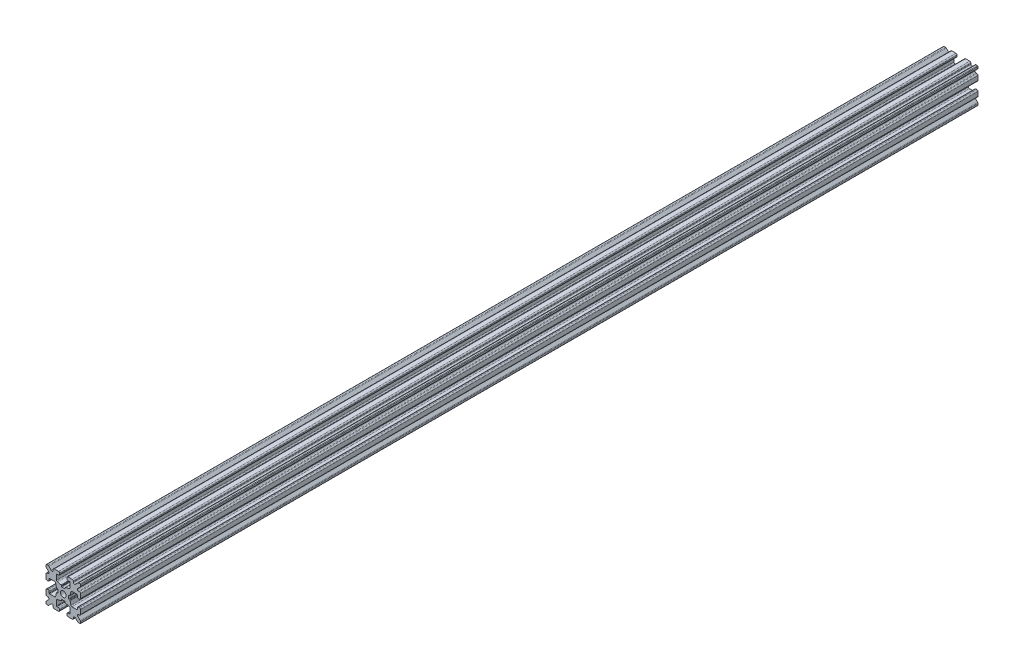
SolidWorks part; units mm, degrees
ref_plane "Alzado" through (0, 0, 0) normal (0, 0, 1) x (1, 0, 0)
ref_plane "Planta" through (0, 0, 0) normal (0, 1, 0) x (1, 0, 0)
ref_plane "Vista lateral" through (0, 0, 0) normal (1, 0, 0) x (0, 0, -1)
ref_plane "Plano1" through (0, 0, -150) normal (0, 0, -1) x (-1, 0, 0)
sketch "Croquis1" plane through (0, 0, -150) normal (0, 0, -1) x (-1, 0, 0)
  line L0 (-2.9, -5.9) -> (-2.9, -3.8003)
  line L1 (-2.5094, -3.3124) -> (-0.9818, -2.97)
  line L2 (-0.8255, -2.7749) -> (-0.8255, -2.5471)
  line L3 (-0.6255, -2.3471) -> (0.6255, -2.3471)
  line L4 (0.8255, -2.5471) -> (0.8255, -2.7749)
  line L5 (0.9818, -2.97) -> (2.5094, -3.3124)
  line L6 (2.9, -3.8003) -> (2.9, -5.9)
  line L7 (2.7, -6.1) -> (2.1, -6.1)
  line L8 (1.6, -6.6) -> (1.6, -7)
  line L9 (2.1, -7.5) -> (3.9, -7.5)
  line L10 (4.4, -7) -> (4.4, -6.6678)
  line L11 (5.2536, -6.3142) -> (6.2929, -7.3536)
  line L12 (6.6464, -7.5) -> (7.25, -7.5)
  line L13 (7.5, -7.25) -> (7.5, -6.6464)
  line L14 (7.3536, -6.2929) -> (6.3142, -5.2536)
  line L15 (6.6678, -4.4) -> (7, -4.4)
  line L16 (7.5, -3.9) -> (7.5, -2.1)
  line L17 (7, -1.6) -> (6.6, -1.6)
  line L18 (6.1, -2.1) -> (6.1, -2.7)
  line L19 (5.9, -2.9) -> (3.8003, -2.9)
  line L20 (3.3124, -2.5094) -> (2.97, -0.9818)
  line L21 (2.7749, -0.8255) -> (2.5471, -0.8255)
  line L22 (2.3471, -0.6255) -> (2.3471, 0.6255)
  line L23 (2.5471, 0.8255) -> (2.7749, 0.8255)
  line L24 (2.97, 0.9818) -> (3.3124, 2.5094)
  line L25 (3.8003, 2.9) -> (5.9, 2.9)
  line L26 (6.1, 2.7) -> (6.1, 2.1)
  line L27 (6.6, 1.6) -> (7, 1.6)
  line L28 (7.5, 2.1) -> (7.5, 3.9)
  line L29 (7, 4.4) -> (6.6678, 4.4)
  line L30 (6.3142, 5.2536) -> (7.3536, 6.2929)
  line L31 (7.5, 6.6464) -> (7.5, 7.25)
  line L32 (7.25, 7.5) -> (6.6464, 7.5)
  line L33 (6.2929, 7.3536) -> (5.2536, 6.3142)
  line L34 (4.4, 6.6678) -> (4.4, 7)
  line L35 (3.9, 7.5) -> (2.1, 7.5)
  line L36 (1.6, 7) -> (1.6, 6.6)
  line L37 (2.1, 6.1) -> (2.7, 6.1)
  line L38 (2.9, 5.9) -> (2.9, 3.8003)
  line L39 (2.5094, 3.3124) -> (0.9818, 2.97)
  line L40 (0.8255, 2.7749) -> (0.8255, 2.5471)
  line L41 (0.6255, 2.3471) -> (-0.6255, 2.3471)
  line L42 (-0.8255, 2.5471) -> (-0.8255, 2.7749)
  line L43 (-0.9818, 2.97) -> (-2.5094, 3.3124)
  line L44 (-2.9, 3.8003) -> (-2.9, 5.9)
  line L45 (-2.7, 6.1) -> (-2.1, 6.1)
  line L46 (-1.6, 6.6) -> (-1.6, 7)
  line L47 (-2.1, 7.5) -> (-3.9, 7.5)
  line L48 (-4.4, 7) -> (-4.4, 6.6678)
  line L49 (-5.2536, 6.3142) -> (-6.2929, 7.3536)
  line L50 (-6.6464, 7.5) -> (-7.25, 7.5)
  line L51 (-7.5, 7.25) -> (-7.5, 6.6464)
  line L52 (-7.3536, 6.2929) -> (-6.3142, 5.2536)
  line L53 (-6.6678, 4.4) -> (-7, 4.4)
  line L54 (-7.5, 3.9) -> (-7.5, 2.1)
  line L55 (-7, 1.6) -> (-6.6, 1.6)
  line L56 (-6.1, 2.1) -> (-6.1, 2.7)
  line L57 (-5.9, 2.9) -> (-3.8003, 2.9)
  line L58 (-3.3124, 2.5094) -> (-2.97, 0.9818)
  line L59 (-2.7749, 0.8255) -> (-2.5471, 0.8255)
  line L60 (-2.3471, 0.6255) -> (-2.3471, -0.6255)
  line L61 (-2.5471, -0.8255) -> (-2.7749, -0.8255)
  line L62 (-2.97, -0.9818) -> (-3.3124, -2.5094)
  line L63 (-3.8003, -2.9) -> (-5.9, -2.9)
  line L64 (-6.1, -2.7) -> (-6.1, -2.1)
  line L65 (-6.6, -1.6) -> (-7, -1.6)
  line L66 (-7.5, -2.1) -> (-7.5, -3.9)
  line L67 (-7, -4.4) -> (-6.6678, -4.4)
  line L68 (-6.3142, -5.2536) -> (-7.3536, -6.2929)
  line L69 (-7.5, -6.6464) -> (-7.5, -7.25)
  line L70 (-7.25, -7.5) -> (-6.6464, -7.5)
  line L71 (-6.2929, -7.3536) -> (-5.2536, -6.3142)
  line L72 (-4.4, -6.6678) -> (-4.4, -7)
  line L73 (-3.9, -7.5) -> (-2.1, -7.5)
  line L74 (-1.6, -7) -> (-1.6, -6.6)
  line L75 (-2.1, -6.1) -> (-2.7, -6.1)
  circle A0 centre (0, 0) radius 1.25
  arc A1 (-2.9, -3.8003) -> (-2.5094, -3.3124) centre (-2.4, -3.8003) cw
  arc A2 (-0.9818, -2.97) -> (-0.8255, -2.7749) centre (-1.0255, -2.7749) ccw
  arc A3 (-0.8255, -2.5471) -> (-0.6255, -2.3471) centre (-0.6255, -2.5471) cw
  arc A4 (0.6255, -2.3471) -> (0.8255, -2.5471) centre (0.6255, -2.5471) cw
  arc A5 (0.8255, -2.7749) -> (0.9818, -2.97) centre (1.0255, -2.7749) ccw
  arc A6 (2.5094, -3.3124) -> (2.9, -3.8003) centre (2.4, -3.8003) cw
  arc A7 (2.9, -5.9) -> (2.7, -6.1) centre (2.7, -5.9) cw
  arc A8 (2.1, -6.1) -> (1.6, -6.6) centre (2.1, -6.6) ccw
  arc A9 (1.6, -7) -> (2.1, -7.5) centre (2.1, -7) ccw
  arc A10 (3.9, -7.5) -> (4.4, -7) centre (3.9, -7) ccw
  arc A11 (4.4, -6.6678) -> (5.2536, -6.3142) centre (4.9, -6.6678) cw
  arc A12 (6.2929, -7.3536) -> (6.6464, -7.5) centre (6.6464, -7) ccw
  arc A13 (7.25, -7.5) -> (7.5, -7.25) centre (7.25, -7.25) ccw
  arc A14 (7.5, -6.6464) -> (7.3536, -6.2929) centre (7, -6.6464) ccw
  arc A15 (6.3142, -5.2536) -> (6.6678, -4.4) centre (6.6678, -4.9) cw
  arc A16 (7, -4.4) -> (7.5, -3.9) centre (7, -3.9) ccw
  arc A17 (7.5, -2.1) -> (7, -1.6) centre (7, -2.1) ccw
  arc A18 (6.6, -1.6) -> (6.1, -2.1) centre (6.6, -2.1) ccw
  arc A19 (6.1, -2.7) -> (5.9, -2.9) centre (5.9, -2.7) cw
  arc A20 (3.8003, -2.9) -> (3.3124, -2.5094) centre (3.8003, -2.4) cw
  arc A21 (2.97, -0.9818) -> (2.7749, -0.8255) centre (2.7749, -1.0255) ccw
  arc A22 (2.5471, -0.8255) -> (2.3471, -0.6255) centre (2.5471, -0.6255) cw
  arc A23 (2.3471, 0.6255) -> (2.5471, 0.8255) centre (2.5471, 0.6255) cw
  arc A24 (2.7749, 0.8255) -> (2.97, 0.9818) centre (2.7749, 1.0255) ccw
  arc A25 (3.3124, 2.5094) -> (3.8003, 2.9) centre (3.8003, 2.4) cw
  arc A26 (5.9, 2.9) -> (6.1, 2.7) centre (5.9, 2.7) cw
  arc A27 (6.1, 2.1) -> (6.6, 1.6) centre (6.6, 2.1) ccw
  arc A28 (7, 1.6) -> (7.5, 2.1) centre (7, 2.1) ccw
  arc A29 (7.5, 3.9) -> (7, 4.4) centre (7, 3.9) ccw
  arc A30 (6.6678, 4.4) -> (6.3142, 5.2536) centre (6.6678, 4.9) cw
  arc A31 (7.3536, 6.2929) -> (7.5, 6.6464) centre (7, 6.6464) ccw
  arc A32 (7.5, 7.25) -> (7.25, 7.5) centre (7.25, 7.25) ccw
  arc A33 (6.6464, 7.5) -> (6.2929, 7.3536) centre (6.6464, 7) ccw
  arc A34 (5.2536, 6.3142) -> (4.4, 6.6678) centre (4.9, 6.6678) cw
  arc A35 (4.4, 7) -> (3.9, 7.5) centre (3.9, 7) ccw
  arc A36 (2.1, 7.5) -> (1.6, 7) centre (2.1, 7) ccw
  arc A37 (1.6, 6.6) -> (2.1, 6.1) centre (2.1, 6.6) ccw
  arc A38 (2.7, 6.1) -> (2.9, 5.9) centre (2.7, 5.9) cw
  arc A39 (2.9, 3.8003) -> (2.5094, 3.3124) centre (2.4, 3.8003) cw
  arc A40 (0.9818, 2.97) -> (0.8255, 2.7749) centre (1.0255, 2.7749) ccw
  arc A41 (0.8255, 2.5471) -> (0.6255, 2.3471) centre (0.6255, 2.5471) cw
  arc A42 (-0.6255, 2.3471) -> (-0.8255, 2.5471) centre (-0.6255, 2.5471) cw
  arc A43 (-0.8255, 2.7749) -> (-0.9818, 2.97) centre (-1.0255, 2.7749) ccw
  arc A44 (-2.5094, 3.3124) -> (-2.9, 3.8003) centre (-2.4, 3.8003) cw
  arc A45 (-2.9, 5.9) -> (-2.7, 6.1) centre (-2.7, 5.9) cw
  arc A46 (-2.1, 6.1) -> (-1.6, 6.6) centre (-2.1, 6.6) ccw
  arc A47 (-1.6, 7) -> (-2.1, 7.5) centre (-2.1, 7) ccw
  arc A48 (-3.9, 7.5) -> (-4.4, 7) centre (-3.9, 7) ccw
  arc A49 (-4.4, 6.6678) -> (-5.2536, 6.3142) centre (-4.9, 6.6678) cw
  arc A50 (-6.2929, 7.3536) -> (-6.6464, 7.5) centre (-6.6464, 7) ccw
  arc A51 (-7.25, 7.5) -> (-7.5, 7.25) centre (-7.25, 7.25) ccw
  arc A52 (-7.5, 6.6464) -> (-7.3536, 6.2929) centre (-7, 6.6464) ccw
  arc A53 (-6.3142, 5.2536) -> (-6.6678, 4.4) centre (-6.6678, 4.9) cw
  arc A54 (-7, 4.4) -> (-7.5, 3.9) centre (-7, 3.9) ccw
  arc A55 (-7.5, 2.1) -> (-7, 1.6) centre (-7, 2.1) ccw
  arc A56 (-6.6, 1.6) -> (-6.1, 2.1) centre (-6.6, 2.1) ccw
  arc A57 (-6.1, 2.7) -> (-5.9, 2.9) centre (-5.9, 2.7) cw
  arc A58 (-3.8003, 2.9) -> (-3.3124, 2.5094) centre (-3.8003, 2.4) cw
  arc A59 (-2.97, 0.9818) -> (-2.7749, 0.8255) centre (-2.7749, 1.0255) ccw
  arc A60 (-2.5471, 0.8255) -> (-2.3471, 0.6255) centre (-2.5471, 0.6255) cw
  arc A61 (-2.3471, -0.6255) -> (-2.5471, -0.8255) centre (-2.5471, -0.6255) cw
  arc A62 (-2.7749, -0.8255) -> (-2.97, -0.9818) centre (-2.7749, -1.0255) ccw
  arc A63 (-3.3124, -2.5094) -> (-3.8003, -2.9) centre (-3.8003, -2.4) cw
  arc A64 (-5.9, -2.9) -> (-6.1, -2.7) centre (-5.9, -2.7) cw
  arc A65 (-6.1, -2.1) -> (-6.6, -1.6) centre (-6.6, -2.1) ccw
  arc A66 (-7, -1.6) -> (-7.5, -2.1) centre (-7, -2.1) ccw
  arc A67 (-7.5, -3.9) -> (-7, -4.4) centre (-7, -3.9) ccw
  arc A68 (-6.6678, -4.4) -> (-6.3142, -5.2536) centre (-6.6678, -4.9) cw
  arc A69 (-7.3536, -6.2929) -> (-7.5, -6.6464) centre (-7, -6.6464) ccw
  arc A70 (-7.5, -7.25) -> (-7.25, -7.5) centre (-7.25, -7.25) ccw
  arc A71 (-6.6464, -7.5) -> (-6.2929, -7.3536) centre (-6.6464, -7) ccw
  arc A72 (-5.2536, -6.3142) -> (-4.4, -6.6678) centre (-4.9, -6.6678) cw
  arc A73 (-4.4, -7) -> (-3.9, -7.5) centre (-3.9, -7) ccw
  arc A74 (-2.1, -7.5) -> (-1.6, -7) centre (-2.1, -7) ccw
  arc A75 (-1.6, -6.6) -> (-2.1, -6.1) centre (-2.1, -6.6) ccw
  arc A76 (-2.7, -6.1) -> (-2.9, -5.9) centre (-2.7, -5.9) cw
extrude "Saliente-Extruir1" add sketch "Croquis1" against normal blind 300
sketch "Croquis2" plane through (0, 0, 150) normal (0, 0, 1) x (1, 0, 0)
  line L76 (2.7, -6.1) -> (2.1, -6.1)
  line L77 (1.6, -6.6) -> (1.6, -7)
  line L78 (2.1, -7.5) -> (3.9, -7.5)
  line L79 (4.4, -7) -> (4.4, -6.6678)
  line L80 (5.2536, -6.3142) -> (6.2929, -7.3536)
  line L81 (6.6464, -7.5) -> (7.25, -7.5)
  line L82 (7.5, -7.25) -> (7.5, -6.6464)
  line L83 (7.3536, -6.2929) -> (6.3142, -5.2536)
  line L84 (6.6678, -4.4) -> (7, -4.4)
  line L85 (7.5, -3.9) -> (7.5, -2.1)
  line L86 (7, -1.6) -> (6.6, -1.6)
  line L87 (6.1, -2.1) -> (6.1, -2.7)
  line L88 (5.9, -2.9) -> (3.8003, -2.9)
  line L89 (3.3124, -2.5094) -> (2.97, -0.9818)
  line L90 (2.7749, -0.8255) -> (2.5471, -0.8255)
  line L91 (2.3471, -0.6255) -> (2.3471, 0.6255)
  line L92 (2.5471, 0.8255) -> (2.7749, 0.8255)
  line L93 (2.97, 0.9818) -> (3.3124, 2.5094)
  line L94 (3.8003, 2.9) -> (5.9, 2.9)
  line L95 (6.1, 2.7) -> (6.1, 2.1)
  line L96 (6.6, 1.6) -> (7, 1.6)
  line L97 (7.5, 2.1) -> (7.5, 3.9)
  line L98 (7, 4.4) -> (6.6678, 4.4)
  line L99 (6.3142, 5.2536) -> (7.3536, 6.2929)
  line L100 (7.5, 6.6464) -> (7.5, 7.25)
  line L101 (7.25, 7.5) -> (6.6464, 7.5)
  line L102 (6.2929, 7.3536) -> (5.2536, 6.3142)
  line L103 (4.4, 6.6678) -> (4.4, 7)
  line L104 (3.9, 7.5) -> (2.1, 7.5)
  line L105 (1.6, 7) -> (1.6, 6.6)
  line L106 (2.1, 6.1) -> (2.7, 6.1)
  line L107 (2.9, 5.9) -> (2.9, 3.8003)
  line L108 (2.5094, 3.3124) -> (0.9818, 2.97)
  line L109 (0.8255, 2.7749) -> (0.8255, 2.5471)
  line L110 (0.6255, 2.3471) -> (-0.6255, 2.3471)
  line L111 (-0.8255, 2.5471) -> (-0.8255, 2.7749)
  line L112 (-0.9818, 2.97) -> (-2.5094, 3.3124)
  line L113 (-2.9, 3.8003) -> (-2.9, 5.9)
  line L114 (-2.7, 6.1) -> (-2.1, 6.1)
  line L115 (-1.6, 6.6) -> (-1.6, 7)
  line L116 (-2.1, 7.5) -> (-3.9, 7.5)
  line L117 (-4.4, 7) -> (-4.4, 6.6678)
  line L118 (-5.2536, 6.3142) -> (-6.2929, 7.3536)
  line L119 (-6.6464, 7.5) -> (-7.25, 7.5)
  line L120 (-7.5, 7.25) -> (-7.5, 6.6464)
  line L121 (-7.3536, 6.2929) -> (-6.3142, 5.2536)
  line L122 (-6.6678, 4.4) -> (-7, 4.4)
  line L123 (-7.5, 3.9) -> (-7.5, 2.1)
  line L124 (-7, 1.6) -> (-6.6, 1.6)
  line L125 (-6.1, 2.1) -> (-6.1, 2.7)
  line L126 (-5.9, 2.9) -> (-3.8003, 2.9)
  line L127 (-3.3124, 2.5094) -> (-2.97, 0.9818)
  line L128 (-2.7749, 0.8255) -> (-2.5471, 0.8255)
  line L129 (-2.3471, 0.6255) -> (-2.3471, -0.6255)
  line L130 (-2.5471, -0.8255) -> (-2.7749, -0.8255)
  line L131 (-2.97, -0.9818) -> (-3.3124, -2.5094)
  line L132 (-3.8003, -2.9) -> (-5.9, -2.9)
  line L133 (-6.1, -2.7) -> (-6.1, -2.1)
  line L134 (-6.6, -1.6) -> (-7, -1.6)
  line L135 (-7.5, -2.1) -> (-7.5, -3.9)
  line L136 (-7, -4.4) -> (-6.6678, -4.4)
  line L137 (-6.3142, -5.2536) -> (-7.3536, -6.2929)
  line L138 (-7.5, -6.6464) -> (-7.5, -7.25)
  line L139 (-7.25, -7.5) -> (-6.6464, -7.5)
  line L140 (-6.2929, -7.3536) -> (-5.2536, -6.3142)
  line L141 (-4.4, -6.6678) -> (-4.4, -7)
  line L142 (-3.9, -7.5) -> (-2.1, -7.5)
  line L143 (-1.6, -7) -> (-1.6, -6.6)
  line L144 (-2.1, -6.1) -> (-2.7, -6.1)
  line L145 (-2.9, -5.9) -> (-2.9, -3.8003)
  line L146 (-2.5094, -3.3124) -> (-0.9818, -2.97)
  line L147 (-0.8255, -2.7749) -> (-0.8255, -2.5471)
  line L148 (-0.6255, -2.3471) -> (0.6255, -2.3471)
  line L149 (0.8255, -2.5471) -> (0.8255, -2.7749)
  line L150 (0.9818, -2.97) -> (2.5094, -3.3124)
  line L151 (2.9, -3.8003) -> (2.9, -5.9)
  line L152 (2.7, -6.1) -> (2.1, -6.1)
  line L153 (1.6, -6.6) -> (1.6, -7)
  line L154 (2.1, -7.5) -> (3.9, -7.5)
  line L155 (4.4, -7) -> (4.4, -6.6678)
  line L156 (5.2536, -6.3142) -> (6.2929, -7.3536)
  line L157 (6.6464, -7.5) -> (7.25, -7.5)
  line L158 (7.5, -7.25) -> (7.5, -6.6464)
  line L159 (7.3536, -6.2929) -> (6.3142, -5.2536)
  line L160 (6.6678, -4.4) -> (7, -4.4)
  line L161 (7.5, -3.9) -> (7.5, -2.1)
  line L162 (7, -1.6) -> (6.6, -1.6)
  line L163 (6.1, -2.1) -> (6.1, -2.7)
  line L164 (5.9, -2.9) -> (3.8003, -2.9)
  line L165 (3.3124, -2.5094) -> (2.97, -0.9818)
  line L166 (2.7749, -0.8255) -> (2.5471, -0.8255)
  line L167 (2.3471, -0.6255) -> (2.3471, 0.6255)
  line L168 (2.5471, 0.8255) -> (2.7749, 0.8255)
  line L169 (2.97, 0.9818) -> (3.3124, 2.5094)
  line L170 (3.8003, 2.9) -> (5.9, 2.9)
  line L171 (6.1, 2.7) -> (6.1, 2.1)
  line L172 (6.6, 1.6) -> (7, 1.6)
  line L173 (7.5, 2.1) -> (7.5, 3.9)
  line L174 (7, 4.4) -> (6.6678, 4.4)
  line L175 (6.3142, 5.2536) -> (7.3536, 6.2929)
  line L176 (7.5, 6.6464) -> (7.5, 7.25)
  line L177 (7.25, 7.5) -> (6.6464, 7.5)
  line L178 (6.2929, 7.3536) -> (5.2536, 6.3142)
  line L179 (4.4, 6.6678) -> (4.4, 7)
  line L180 (3.9, 7.5) -> (2.1, 7.5)
  line L181 (1.6, 7) -> (1.6, 6.6)
  line L182 (2.1, 6.1) -> (2.7, 6.1)
  line L183 (2.9, 5.9) -> (2.9, 3.8003)
  line L184 (2.5094, 3.3124) -> (0.9818, 2.97)
  line L185 (0.8255, 2.7749) -> (0.8255, 2.5471)
  line L186 (0.6255, 2.3471) -> (-0.6255, 2.3471)
  line L187 (-0.8255, 2.5471) -> (-0.8255, 2.7749)
  line L188 (-0.9818, 2.97) -> (-2.5094, 3.3124)
  line L189 (-2.9, 3.8003) -> (-2.9, 5.9)
  line L190 (-2.7, 6.1) -> (-2.1, 6.1)
  line L191 (-1.6, 6.6) -> (-1.6, 7)
  line L192 (-2.1, 7.5) -> (-3.9, 7.5)
  line L193 (-4.4, 7) -> (-4.4, 6.6678)
  line L194 (-5.2536, 6.3142) -> (-6.2929, 7.3536)
  line L195 (-6.6464, 7.5) -> (-7.25, 7.5)
  line L196 (-7.5, 7.25) -> (-7.5, 6.6464)
  line L197 (-7.3536, 6.2929) -> (-6.3142, 5.2536)
  line L198 (-6.6678, 4.4) -> (-7, 4.4)
  line L199 (-7.5, 3.9) -> (-7.5, 2.1)
  line L200 (-7, 1.6) -> (-6.6, 1.6)
  line L201 (-6.1, 2.1) -> (-6.1, 2.7)
  line L202 (-5.9, 2.9) -> (-3.8003, 2.9)
  line L203 (-3.3124, 2.5094) -> (-2.97, 0.9818)
  line L204 (-2.7749, 0.8255) -> (-2.5471, 0.8255)
  line L205 (-2.3471, 0.6255) -> (-2.3471, -0.6255)
  line L206 (-2.5471, -0.8255) -> (-2.7749, -0.8255)
  line L207 (-2.97, -0.9818) -> (-3.3124, -2.5094)
  line L208 (-3.8003, -2.9) -> (-5.9, -2.9)
  line L209 (-6.1, -2.7) -> (-6.1, -2.1)
  line L210 (-6.6, -1.6) -> (-7, -1.6)
  line L211 (-7.5, -2.1) -> (-7.5, -3.9)
  line L212 (-7, -4.4) -> (-6.6678, -4.4)
  line L213 (-6.3142, -5.2536) -> (-7.3536, -6.2929)
  line L214 (-7.5, -6.6464) -> (-7.5, -7.25)
  line L215 (-7.25, -7.5) -> (-6.6464, -7.5)
  line L216 (-6.2929, -7.3536) -> (-5.2536, -6.3142)
  line L217 (-4.4, -6.6678) -> (-4.4, -7)
  line L218 (-3.9, -7.5) -> (-2.1, -7.5)
  line L219 (-1.6, -7) -> (-1.6, -6.6)
  line L220 (-2.1, -6.1) -> (-2.7, -6.1)
  line L221 (-2.9, -5.9) -> (-2.9, -3.8003)
  line L222 (-2.5094, -3.3124) -> (-0.9818, -2.97)
  line L223 (-0.8255, -2.7749) -> (-0.8255, -2.5471)
  line L224 (-0.6255, -2.3471) -> (0.6255, -2.3471)
  line L225 (0.8255, -2.5471) -> (0.8255, -2.7749)
  line L226 (0.9818, -2.97) -> (2.5094, -3.3124)
  line L227 (2.9, -3.8003) -> (2.9, -5.9)
  circle A0 centre (0, 0) radius 1.25 construction
  circle A1 centre (0, 0) radius 1.25
  arc A76 (2.7, -6.1) -> (2.9, -5.9) centre (2.7, -5.9) ccw
  arc A77 (2.1, -6.1) -> (1.6, -6.6) centre (2.1, -6.6) ccw
  arc A78 (1.6, -7) -> (2.1, -7.5) centre (2.1, -7) ccw
  arc A79 (3.9, -7.5) -> (4.4, -7) centre (3.9, -7) ccw
  arc A80 (5.2536, -6.3142) -> (4.4, -6.6678) centre (4.9, -6.6678) ccw
  arc A81 (6.2929, -7.3536) -> (6.6464, -7.5) centre (6.6464, -7) ccw
  arc A82 (7.25, -7.5) -> (7.5, -7.25) centre (7.25, -7.25) ccw
  arc A83 (7.5, -6.6464) -> (7.3536, -6.2929) centre (7, -6.6464) ccw
  arc A84 (6.6678, -4.4) -> (6.3142, -5.2536) centre (6.6678, -4.9) ccw
  arc A85 (7, -4.4) -> (7.5, -3.9) centre (7, -3.9) ccw
  arc A86 (7.5, -2.1) -> (7, -1.6) centre (7, -2.1) ccw
  arc A87 (6.6, -1.6) -> (6.1, -2.1) centre (6.6, -2.1) ccw
  arc A88 (5.9, -2.9) -> (6.1, -2.7) centre (5.9, -2.7) ccw
  arc A89 (3.3124, -2.5094) -> (3.8003, -2.9) centre (3.8003, -2.4) ccw
  arc A90 (2.97, -0.9818) -> (2.7749, -0.8255) centre (2.7749, -1.0255) ccw
  arc A91 (2.3471, -0.6255) -> (2.5471, -0.8255) centre (2.5471, -0.6255) ccw
  arc A92 (2.5471, 0.8255) -> (2.3471, 0.6255) centre (2.5471, 0.6255) ccw
  arc A93 (2.7749, 0.8255) -> (2.97, 0.9818) centre (2.7749, 1.0255) ccw
  arc A94 (3.8003, 2.9) -> (3.3124, 2.5094) centre (3.8003, 2.4) ccw
  arc A95 (6.1, 2.7) -> (5.9, 2.9) centre (5.9, 2.7) ccw
  arc A96 (6.1, 2.1) -> (6.6, 1.6) centre (6.6, 2.1) ccw
  arc A97 (7, 1.6) -> (7.5, 2.1) centre (7, 2.1) ccw
  arc A98 (7.5, 3.9) -> (7, 4.4) centre (7, 3.9) ccw
  arc A99 (6.3142, 5.2536) -> (6.6678, 4.4) centre (6.6678, 4.9) ccw
  arc A100 (7.3536, 6.2929) -> (7.5, 6.6464) centre (7, 6.6464) ccw
  arc A101 (7.5, 7.25) -> (7.25, 7.5) centre (7.25, 7.25) ccw
  arc A102 (6.6464, 7.5) -> (6.2929, 7.3536) centre (6.6464, 7) ccw
  arc A103 (4.4, 6.6678) -> (5.2536, 6.3142) centre (4.9, 6.6678) ccw
  arc A104 (4.4, 7) -> (3.9, 7.5) centre (3.9, 7) ccw
  arc A105 (2.1, 7.5) -> (1.6, 7) centre (2.1, 7) ccw
  arc A106 (1.6, 6.6) -> (2.1, 6.1) centre (2.1, 6.6) ccw
  arc A107 (2.9, 5.9) -> (2.7, 6.1) centre (2.7, 5.9) ccw
  arc A108 (2.5094, 3.3124) -> (2.9, 3.8003) centre (2.4, 3.8003) ccw
  arc A109 (0.9818, 2.97) -> (0.8255, 2.7749) centre (1.0255, 2.7749) ccw
  arc A110 (0.6255, 2.3471) -> (0.8255, 2.5471) centre (0.6255, 2.5471) ccw
  arc A111 (-0.8255, 2.5471) -> (-0.6255, 2.3471) centre (-0.6255, 2.5471) ccw
  arc A112 (-0.8255, 2.7749) -> (-0.9818, 2.97) centre (-1.0255, 2.7749) ccw
  arc A113 (-2.9, 3.8003) -> (-2.5094, 3.3124) centre (-2.4, 3.8003) ccw
  arc A114 (-2.7, 6.1) -> (-2.9, 5.9) centre (-2.7, 5.9) ccw
  arc A115 (-2.1, 6.1) -> (-1.6, 6.6) centre (-2.1, 6.6) ccw
  arc A116 (-1.6, 7) -> (-2.1, 7.5) centre (-2.1, 7) ccw
  arc A117 (-3.9, 7.5) -> (-4.4, 7) centre (-3.9, 7) ccw
  arc A118 (-5.2536, 6.3142) -> (-4.4, 6.6678) centre (-4.9, 6.6678) ccw
  arc A119 (-6.2929, 7.3536) -> (-6.6464, 7.5) centre (-6.6464, 7) ccw
  arc A120 (-7.25, 7.5) -> (-7.5, 7.25) centre (-7.25, 7.25) ccw
  arc A121 (-7.5, 6.6464) -> (-7.3536, 6.2929) centre (-7, 6.6464) ccw
  arc A122 (-6.6678, 4.4) -> (-6.3142, 5.2536) centre (-6.6678, 4.9) ccw
  arc A123 (-7, 4.4) -> (-7.5, 3.9) centre (-7, 3.9) ccw
  arc A124 (-7.5, 2.1) -> (-7, 1.6) centre (-7, 2.1) ccw
  arc A125 (-6.6, 1.6) -> (-6.1, 2.1) centre (-6.6, 2.1) ccw
  arc A126 (-5.9, 2.9) -> (-6.1, 2.7) centre (-5.9, 2.7) ccw
  arc A127 (-3.3124, 2.5094) -> (-3.8003, 2.9) centre (-3.8003, 2.4) ccw
  arc A128 (-2.97, 0.9818) -> (-2.7749, 0.8255) centre (-2.7749, 1.0255) ccw
  arc A129 (-2.3471, 0.6255) -> (-2.5471, 0.8255) centre (-2.5471, 0.6255) ccw
  arc A130 (-2.5471, -0.8255) -> (-2.3471, -0.6255) centre (-2.5471, -0.6255) ccw
  arc A131 (-2.7749, -0.8255) -> (-2.97, -0.9818) centre (-2.7749, -1.0255) ccw
  arc A132 (-3.8003, -2.9) -> (-3.3124, -2.5094) centre (-3.8003, -2.4) ccw
  arc A133 (-6.1, -2.7) -> (-5.9, -2.9) centre (-5.9, -2.7) ccw
  arc A134 (-6.1, -2.1) -> (-6.6, -1.6) centre (-6.6, -2.1) ccw
  arc A135 (-7, -1.6) -> (-7.5, -2.1) centre (-7, -2.1) ccw
  arc A136 (-7.5, -3.9) -> (-7, -4.4) centre (-7, -3.9) ccw
  arc A137 (-6.3142, -5.2536) -> (-6.6678, -4.4) centre (-6.6678, -4.9) ccw
  arc A138 (-7.3536, -6.2929) -> (-7.5, -6.6464) centre (-7, -6.6464) ccw
  arc A139 (-7.5, -7.25) -> (-7.25, -7.5) centre (-7.25, -7.25) ccw
  arc A140 (-6.6464, -7.5) -> (-6.2929, -7.3536) centre (-6.6464, -7) ccw
  arc A141 (-4.4, -6.6678) -> (-5.2536, -6.3142) centre (-4.9, -6.6678) ccw
  arc A142 (-4.4, -7) -> (-3.9, -7.5) centre (-3.9, -7) ccw
  arc A143 (-2.1, -7.5) -> (-1.6, -7) centre (-2.1, -7) ccw
  arc A144 (-1.6, -6.6) -> (-2.1, -6.1) centre (-2.1, -6.6) ccw
  arc A145 (-2.9, -5.9) -> (-2.7, -6.1) centre (-2.7, -5.9) ccw
  arc A146 (-2.5094, -3.3124) -> (-2.9, -3.8003) centre (-2.4, -3.8003) ccw
  arc A147 (-0.9818, -2.97) -> (-0.8255, -2.7749) centre (-1.0255, -2.7749) ccw
  arc A148 (-0.6255, -2.3471) -> (-0.8255, -2.5471) centre (-0.6255, -2.5471) ccw
  arc A149 (0.8255, -2.5471) -> (0.6255, -2.3471) centre (0.6255, -2.5471) ccw
  arc A150 (0.8255, -2.7749) -> (0.9818, -2.97) centre (1.0255, -2.7749) ccw
  arc A151 (2.9, -3.8003) -> (2.5094, -3.3124) centre (2.4, -3.8003) ccw
  arc A152 (2.7, -6.1) -> (2.9, -5.9) centre (2.7, -5.9) ccw
  arc A153 (2.1, -6.1) -> (1.6, -6.6) centre (2.1, -6.6) ccw
  arc A154 (1.6, -7) -> (2.1, -7.5) centre (2.1, -7) ccw
  arc A155 (3.9, -7.5) -> (4.4, -7) centre (3.9, -7) ccw
  arc A156 (5.2536, -6.3142) -> (4.4, -6.6678) centre (4.9, -6.6678) ccw
  arc A157 (6.2929, -7.3536) -> (6.6464, -7.5) centre (6.6464, -7) ccw
  arc A158 (7.25, -7.5) -> (7.5, -7.25) centre (7.25, -7.25) ccw
  arc A159 (7.5, -6.6464) -> (7.3536, -6.2929) centre (7, -6.6464) ccw
  arc A160 (6.6678, -4.4) -> (6.3142, -5.2536) centre (6.6678, -4.9) ccw
  arc A161 (7, -4.4) -> (7.5, -3.9) centre (7, -3.9) ccw
  arc A162 (7.5, -2.1) -> (7, -1.6) centre (7, -2.1) ccw
  arc A163 (6.6, -1.6) -> (6.1, -2.1) centre (6.6, -2.1) ccw
  arc A164 (5.9, -2.9) -> (6.1, -2.7) centre (5.9, -2.7) ccw
  arc A165 (3.3124, -2.5094) -> (3.8003, -2.9) centre (3.8003, -2.4) ccw
  arc A166 (2.97, -0.9818) -> (2.7749, -0.8255) centre (2.7749, -1.0255) ccw
  arc A167 (2.3471, -0.6255) -> (2.5471, -0.8255) centre (2.5471, -0.6255) ccw
  arc A168 (2.5471, 0.8255) -> (2.3471, 0.6255) centre (2.5471, 0.6255) ccw
  arc A169 (2.7749, 0.8255) -> (2.97, 0.9818) centre (2.7749, 1.0255) ccw
  arc A170 (3.8003, 2.9) -> (3.3124, 2.5094) centre (3.8003, 2.4) ccw
  arc A171 (6.1, 2.7) -> (5.9, 2.9) centre (5.9, 2.7) ccw
  arc A172 (6.1, 2.1) -> (6.6, 1.6) centre (6.6, 2.1) ccw
  arc A173 (7, 1.6) -> (7.5, 2.1) centre (7, 2.1) ccw
  arc A174 (7.5, 3.9) -> (7, 4.4) centre (7, 3.9) ccw
  arc A175 (6.3142, 5.2536) -> (6.6678, 4.4) centre (6.6678, 4.9) ccw
  arc A176 (7.3536, 6.2929) -> (7.5, 6.6464) centre (7, 6.6464) ccw
  arc A177 (7.5, 7.25) -> (7.25, 7.5) centre (7.25, 7.25) ccw
  arc A178 (6.6464, 7.5) -> (6.2929, 7.3536) centre (6.6464, 7) ccw
  arc A179 (4.4, 6.6678) -> (5.2536, 6.3142) centre (4.9, 6.6678) ccw
  arc A180 (4.4, 7) -> (3.9, 7.5) centre (3.9, 7) ccw
  arc A181 (2.1, 7.5) -> (1.6, 7) centre (2.1, 7) ccw
  arc A182 (1.6, 6.6) -> (2.1, 6.1) centre (2.1, 6.6) ccw
  arc A183 (2.9, 5.9) -> (2.7, 6.1) centre (2.7, 5.9) ccw
  arc A184 (2.5094, 3.3124) -> (2.9, 3.8003) centre (2.4, 3.8003) ccw
  arc A185 (0.9818, 2.97) -> (0.8255, 2.7749) centre (1.0255, 2.7749) ccw
  arc A186 (0.6255, 2.3471) -> (0.8255, 2.5471) centre (0.6255, 2.5471) ccw
  arc A187 (-0.8255, 2.5471) -> (-0.6255, 2.3471) centre (-0.6255, 2.5471) ccw
  arc A188 (-0.8255, 2.7749) -> (-0.9818, 2.97) centre (-1.0255, 2.7749) ccw
  arc A189 (-2.9, 3.8003) -> (-2.5094, 3.3124) centre (-2.4, 3.8003) ccw
  arc A190 (-2.7, 6.1) -> (-2.9, 5.9) centre (-2.7, 5.9) ccw
  arc A191 (-2.1, 6.1) -> (-1.6, 6.6) centre (-2.1, 6.6) ccw
  arc A192 (-1.6, 7) -> (-2.1, 7.5) centre (-2.1, 7) ccw
  arc A193 (-3.9, 7.5) -> (-4.4, 7) centre (-3.9, 7) ccw
  arc A194 (-5.2536, 6.3142) -> (-4.4, 6.6678) centre (-4.9, 6.6678) ccw
  arc A195 (-6.2929, 7.3536) -> (-6.6464, 7.5) centre (-6.6464, 7) ccw
  arc A196 (-7.25, 7.5) -> (-7.5, 7.25) centre (-7.25, 7.25) ccw
  arc A197 (-7.5, 6.6464) -> (-7.3536, 6.2929) centre (-7, 6.6464) ccw
  arc A198 (-6.6678, 4.4) -> (-6.3142, 5.2536) centre (-6.6678, 4.9) ccw
  arc A199 (-7, 4.4) -> (-7.5, 3.9) centre (-7, 3.9) ccw
  arc A200 (-7.5, 2.1) -> (-7, 1.6) centre (-7, 2.1) ccw
  arc A201 (-6.6, 1.6) -> (-6.1, 2.1) centre (-6.6, 2.1) ccw
  arc A202 (-5.9, 2.9) -> (-6.1, 2.7) centre (-5.9, 2.7) ccw
  arc A203 (-3.3124, 2.5094) -> (-3.8003, 2.9) centre (-3.8003, 2.4) ccw
  arc A204 (-2.97, 0.9818) -> (-2.7749, 0.8255) centre (-2.7749, 1.0255) ccw
  arc A205 (-2.3471, 0.6255) -> (-2.5471, 0.8255) centre (-2.5471, 0.6255) ccw
  arc A206 (-2.5471, -0.8255) -> (-2.3471, -0.6255) centre (-2.5471, -0.6255) ccw
  arc A207 (-2.7749, -0.8255) -> (-2.97, -0.9818) centre (-2.7749, -1.0255) ccw
  arc A208 (-3.8003, -2.9) -> (-3.3124, -2.5094) centre (-3.8003, -2.4) ccw
  arc A209 (-6.1, -2.7) -> (-5.9, -2.9) centre (-5.9, -2.7) ccw
  arc A210 (-6.1, -2.1) -> (-6.6, -1.6) centre (-6.6, -2.1) ccw
  arc A211 (-7, -1.6) -> (-7.5, -2.1) centre (-7, -2.1) ccw
  arc A212 (-7.5, -3.9) -> (-7, -4.4) centre (-7, -3.9) ccw
  arc A213 (-6.3142, -5.2536) -> (-6.6678, -4.4) centre (-6.6678, -4.9) ccw
  arc A214 (-7.3536, -6.2929) -> (-7.5, -6.6464) centre (-7, -6.6464) ccw
  arc A215 (-7.5, -7.25) -> (-7.25, -7.5) centre (-7.25, -7.25) ccw
  arc A216 (-6.6464, -7.5) -> (-6.2929, -7.3536) centre (-6.6464, -7) ccw
  arc A217 (-4.4, -6.6678) -> (-5.2536, -6.3142) centre (-4.9, -6.6678) ccw
  arc A218 (-4.4, -7) -> (-3.9, -7.5) centre (-3.9, -7) ccw
  arc A219 (-2.1, -7.5) -> (-1.6, -7) centre (-2.1, -7) ccw
  arc A220 (-1.6, -6.6) -> (-2.1, -6.1) centre (-2.1, -6.6) ccw
  arc A221 (-2.9, -5.9) -> (-2.7, -6.1) centre (-2.7, -5.9) ccw
  arc A222 (-2.5094, -3.3124) -> (-2.9, -3.8003) centre (-2.4, -3.8003) ccw
  arc A223 (-0.9818, -2.97) -> (-0.8255, -2.7749) centre (-1.0255, -2.7749) ccw
  arc A224 (-0.6255, -2.3471) -> (-0.8255, -2.5471) centre (-0.6255, -2.5471) ccw
  arc A225 (0.8255, -2.5471) -> (0.6255, -2.3471) centre (0.6255, -2.5471) ccw
  arc A226 (0.8255, -2.7749) -> (0.9818, -2.97) centre (1.0255, -2.7749) ccw
  arc A227 (2.9, -3.8003) -> (2.5094, -3.3124) centre (2.4, -3.8003) ccw
  dimension "D1" = 0
extrude "Saliente-Extruir2" add sketch "Croquis2" along normal blind 90
